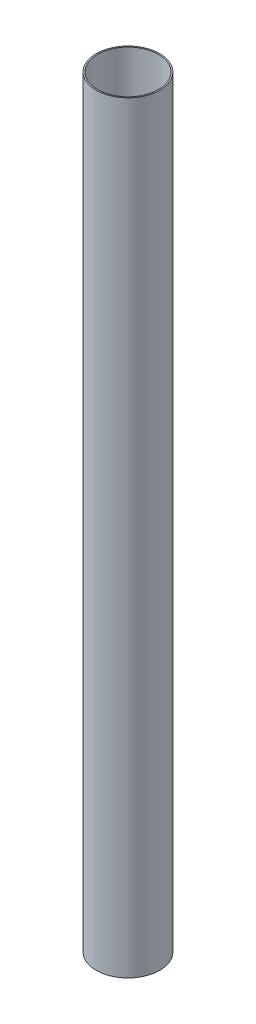
SolidWorks part; units mm, degrees
ref_plane "Plan de face" through (0, 0, 0) normal (0, 0, 1) x (1, 0, 0)
ref_plane "Plan de dessus" through (0, 0, 0) normal (0, 1, 0) x (1, 0, 0)
ref_plane "Plan de droite" through (0, 0, 0) normal (1, 0, 0) x (0, 0, -1)
sketch "Esquisse2" plane through (0, 0, 0) normal (0, 1, 0) x (1, 0, 0)
  circle A0 centre (-6.5488, -11.4039) radius 60
  circle A1 centre (-6.5488, -11.4039) radius 62.5
  dimension "D1" = 120
  dimension "D2" = 125
extrude "Boss.-Extru.1" add sketch "Esquisse2" along normal blind 1500
